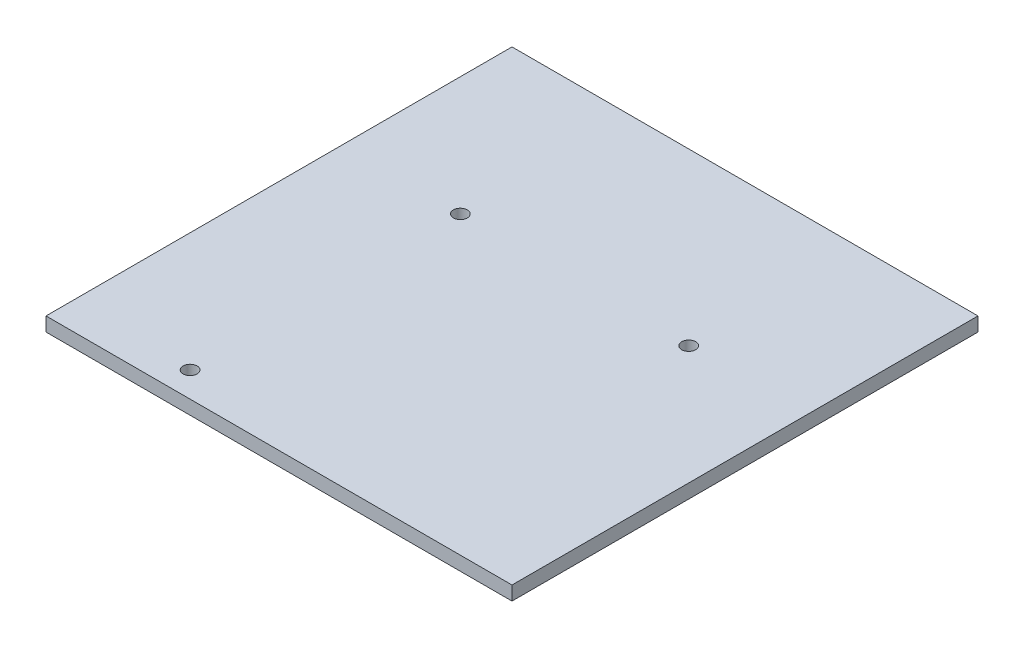
SolidWorks part; units mm, degrees
ref_plane "Alzado" through (0, 0, 0) normal (0, 0, 1) x (1, 0, 0)
ref_plane "Planta" through (0, 0, 0) normal (0, 1, 0) x (1, 0, 0)
ref_plane "Vista lateral" through (0, 0, 0) normal (1, 0, 0) x (0, 0, -1)
sketch "Croquis1" plane through (0, 0, 0) normal (0, 1, 0) x (1, 0, 0)
  line L1 (-50, -50) -> (50, -50)
  line L2 (-50, -50) -> (-50, 50)
  line L3 (-50, 50) -> (50, 50)
  line L4 (50, -50) -> (50, 50)
  line L5 (-50, -50) -> (50, 50) construction
  line L6 (-50, 50) -> (50, -50) construction
  circle A0 centre (-24.5, 13.4228) radius 1.5
  circle A1 centre (24.5, 13.4228) radius 1.5
  circle A2 centre (-24.5, -44.5772) radius 1.5
  point P0 (0, 0)
  dimension "D1" = 100
  dimension "D2" = 100
extrude "Saliente-Extruir1" add sketch "Croquis1" along normal blind 3
